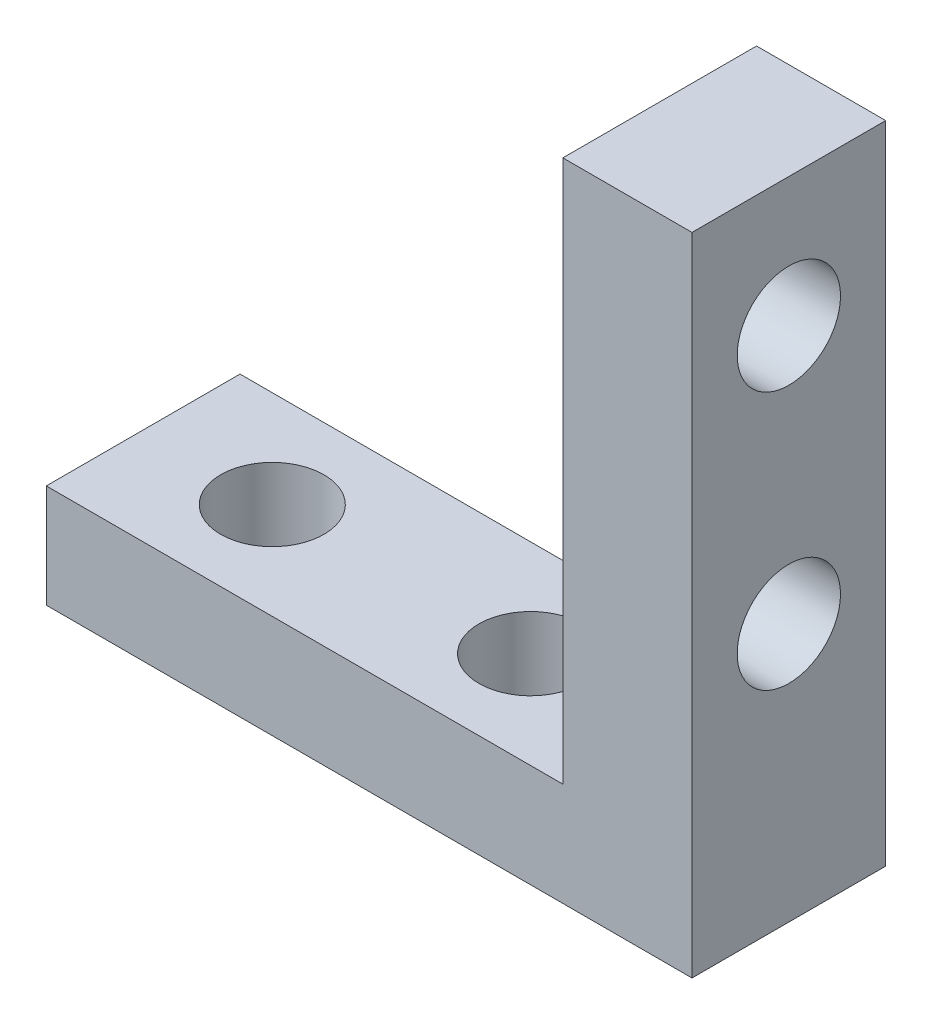
SolidWorks part; units mm, degrees
ref_plane "Front Plane" through (0, 0, 0) normal (0, 0, 1) x (1, 0, 0)
ref_plane "Top Plane" through (0, 0, 0) normal (0, 1, 0) x (1, 0, 0)
ref_plane "Right Plane" through (0, 0, 0) normal (1, 0, 0) x (0, 0, -1)
sketch "Sketch1" plane through (0, 0, 0) normal (0, 1, 0) x (1, 0, 0)
  line L1 (-15, 3.75) -> (5, 3.75)
  line L2 (-15, 3.75) -> (-15, -3.75)
  line L3 (-15, -3.75) -> (5, -3.75)
  line L4 (5, 3.75) -> (5, -3.75)
  circle A0 centre (0, 0) radius 2
  circle A1 centre (-10, 0) radius 2
  dimension "D1" = 4
  dimension "D2" = 4
  dimension "D3" = 10
  dimension "D6" = 5
  dimension "D4" = 7.5
  dimension "D5" = 3.75
  dimension "D7" = 5
extrude "Boss-Extrude1" add sketch "Sketch1" along normal blind 4
sketch "Sketch2" plane through (5, 0, 0) normal (1, 0, 0) x (0, 0, -1)
  line L1 (-3.75, 0) -> (3.75, 0)
  line L2 (-3.75, 0) -> (-3.75, 25)
  line L3 (-3.75, 25) -> (3.75, 25)
  line L4 (3.75, 0) -> (3.75, 25)
  circle A0 centre (0, 20) radius 2
  circle A1 centre (0, 10) radius 2
  dimension "D2" = 4
  dimension "D3" = 4
  dimension "D4" = 5
  dimension "D5" = 10
  dimension "D6" = 10
  dimension "D1" = 7.5
extrude "Boss-Extrude2" add sketch "Sketch2" along normal blind 5
